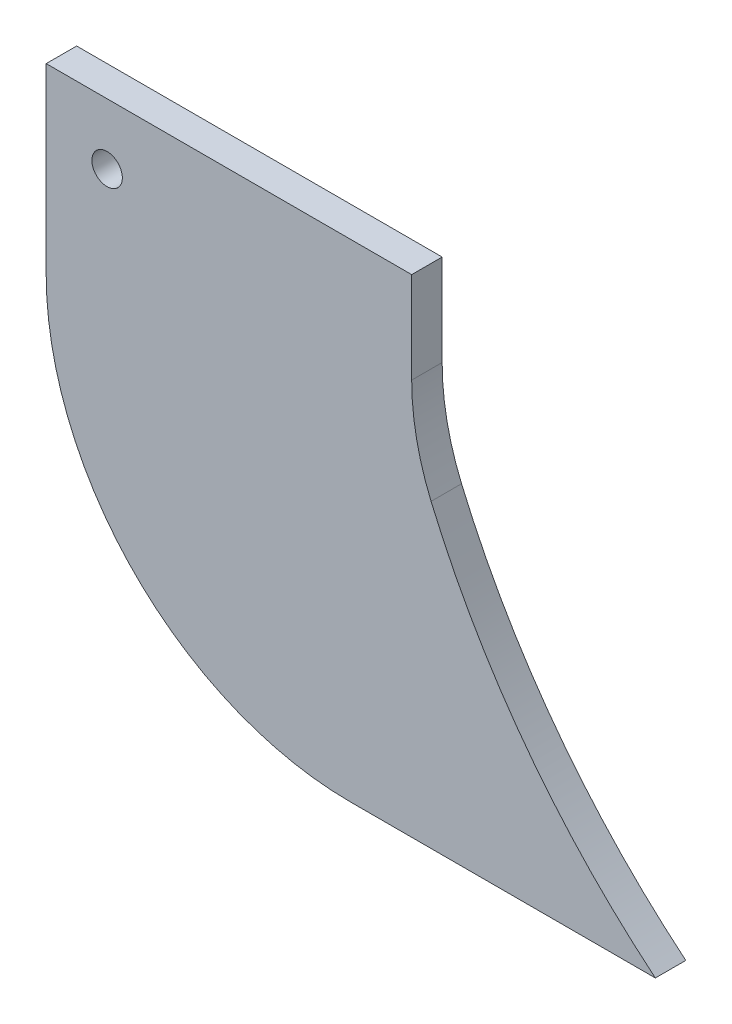
SolidWorks part; units mm, degrees
ref_plane "Front Plane" through (0, 0, 0) normal (0, 0, 1) x (1, 0, 0)
ref_plane "Top Plane" through (0, 0, 0) normal (0, 1, 0) x (1, 0, 0)
ref_plane "Right Plane" through (0, 0, 0) normal (1, 0, 0) x (0, 0, -1)
sketch "Sketch1" plane through (0, 0, 0) normal (0, 0, 1) x (1, 0, 0)
  line L0 (63.5, 0) -> (127, 0)
  line L1 (0, 63.5) -> (0, 101.6)
  line L5 (0, 101.6) -> (76.2, 101.6)
  line L6 (76.2, 101.6) -> (76.2, 82.55)
  arc A0 (80.2447, 62.6859) -> (127, 0) centre (232.1994, 127.2442) ccw
  circle A1 centre (12.7, 88.9) radius 3.175
  arc A2 (63.5, 0) -> (0, 63.5) centre (63.5, 63.5) cw
  arc A3 (76.2, 82.55) -> (80.2447, 62.6859) centre (127, 82.55) ccw
  point P12 (0, 0)
  dimension "D3" = 165.1
  dimension "D4" = 63.5
  dimension "D5" = 50.8
  dimension "D7" = 19.05
  dimension "D8" = 6.35
  dimension "D9" = 12.7
  dimension "D1" = 127
  dimension "D2" = 101.6
  dimension "D6" = 76.2
  dimension "D10" = 12.7
extrude "Boss-Extrude1" add sketch "Sketch1" along normal blind 6.35
